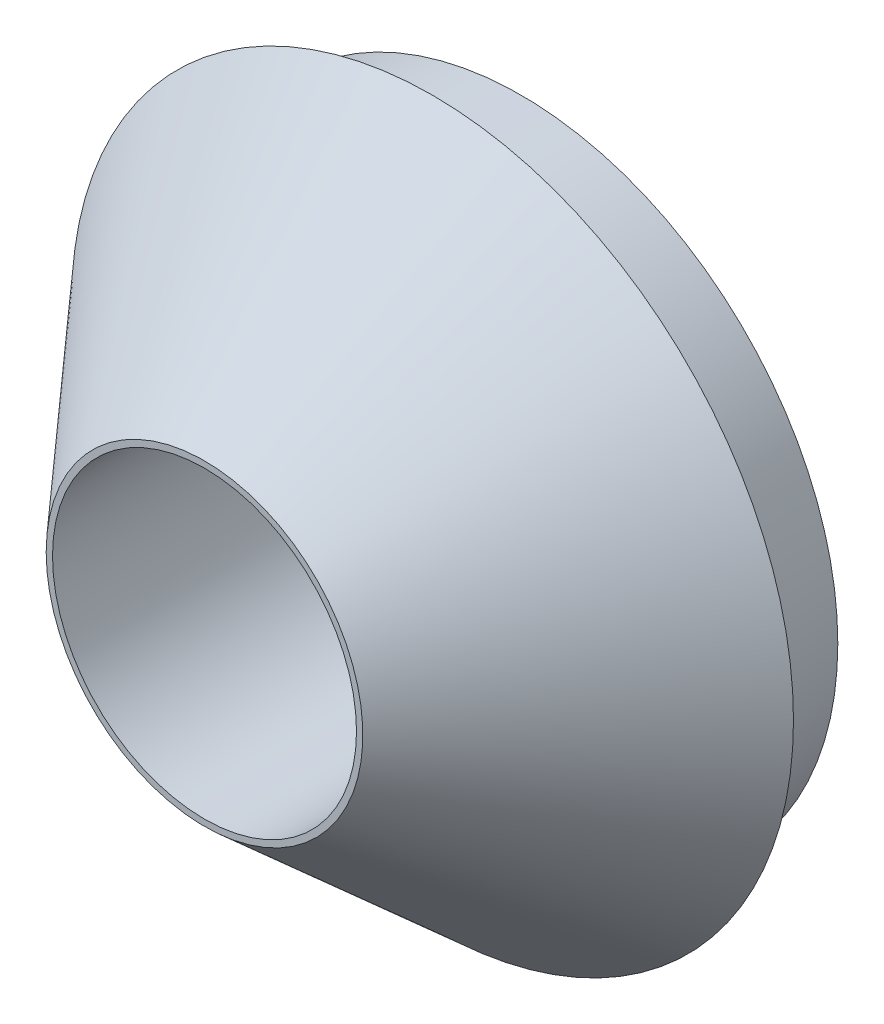
SolidWorks part; units mm, degrees
ref_plane "Front Plane" through (0, 0, 0) normal (0, 0, 1) x (1, 0, 0)
ref_plane "Top Plane" through (0, 0, 0) normal (0, 1, 0) x (1, 0, 0)
ref_plane "Right Plane" through (0, 0, 0) normal (1, 0, 0) x (0, 0, -1)
sketch "Sketch1" plane through (0, 0, 0) normal (0, 1, 0) x (1, 0, 0)
  line L0 (0, 0) -> (6.35, 0)
  line L1 (6.35, 0) -> (14.478, 9.144)
  line L2 (14.478, 9.144) -> (12.7, 9.144)
  line L3 (12.7, 9.144) -> (12.7, 12.7)
  line L4 (12.7, 12.7) -> (0, 12.7)
  line L5 (0, 12.7) -> (0, 0)
  dimension "D1" = 6.35
  dimension "D2" = 12.7
  dimension "D3" = 12.7
  dimension "D4" = 1.778
  dimension "D5" = 3.556
revolve "Revolve1" add sketch "Sketch1" angle 360 about L5
sketch "Sketch2" plane through (0, 0, -12.7) normal (0, 0, -1) x (-1, 0, 0)
  circle A0 centre (0, 0) radius 6.096
  dimension "D1" = 12.192
extrude "Cut-Extrude1" cut sketch "Sketch2" against normal blind 12.7
